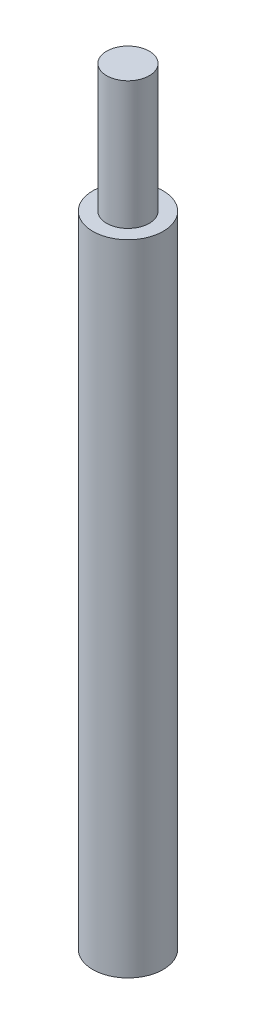
SolidWorks part; units mm, degrees
ref_plane "Front Plane" through (0, 0, 0) normal (0, 0, 1) x (1, 0, 0)
ref_plane "Top Plane" through (0, 0, 0) normal (0, 1, 0) x (1, 0, 0)
ref_plane "Right Plane" through (0, 0, 0) normal (1, 0, 0) x (0, 0, -1)
sketch "Sketch1" plane through (0, 0, 0) normal (0, 1, 0) x (1, 0, 0)
  circle A0 centre (0, 0) radius 1.65
  point P3 (0, 0)
  dimension "D1" = 3.3
extrude "Boss-Extrude1" add sketch "Sketch1" along normal blind 30
sketch "Sketch2" plane through (0, 30, 0) normal (0, 1, 0) x (1, 0, 0)
  circle A0 centre (0, 0) radius 1
  dimension "D1" = 2
extrude "Boss-Extrude2" add sketch "Sketch2" along normal blind 6
